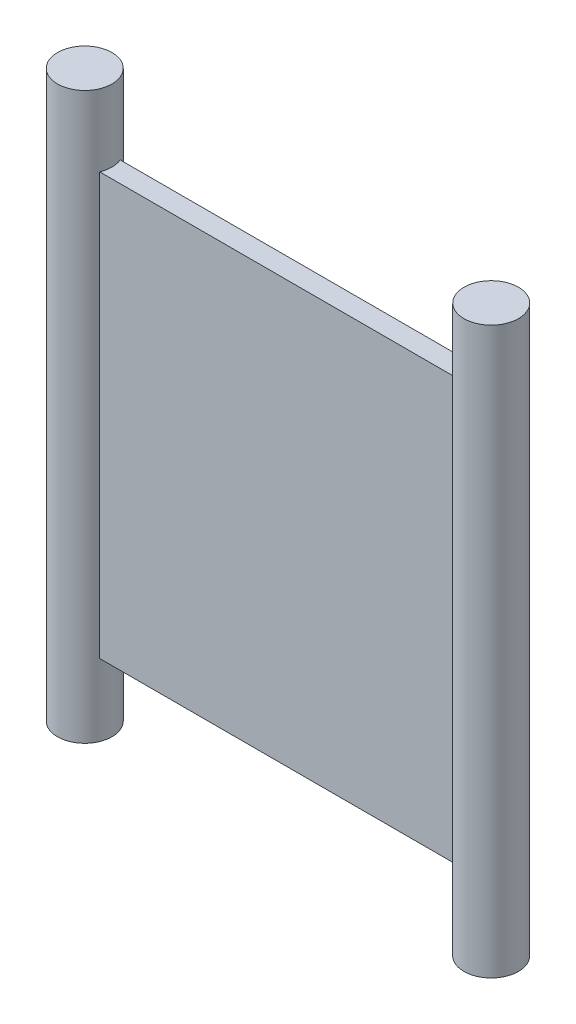
SolidWorks part; units mm, degrees
ref_plane "Front Plane" through (0, 0, 0) normal (0, 0, 1) x (1, 0, 0)
ref_plane "Top Plane" through (0, 0, 0) normal (0, 1, 0) x (1, 0, 0)
ref_plane "Right Plane" through (0, 0, 0) normal (1, 0, 0) x (0, 0, -1)
sketch "Sketch1" plane through (0, 0, 0) normal (0, 1, 0) x (1, 0, 0)
  line L1 (9.885, 0.5) -> (-9.885, 0.5)
  line L2 (9.885, 0.5) -> (9.885, -0.5)
  line L3 (9.885, -0.5) -> (-9.885, -0.5)
  line L4 (-9.885, 0.5) -> (-9.885, -0.5)
  line L5 (9.885, 0.5) -> (-9.885, -0.5) construction
  line L6 (9.885, -0.5) -> (-9.885, 0.5) construction
  point P0 (0, 0)
  dimension "D1" = 19.77
  dimension "D3" = 1
extrude "Boss-Extrude1" add sketch "Sketch1" along normal blind 20.5
ref_plane "Plane1" through (0, 10.25, 0) normal (0, 1, 0) x (1, 0, 0)
sketch "Sketch2" plane through (0, 10.25, 0) normal (0, 1, 0) x (1, 0, 0)
  line L0 (9.885, -0.5) -> (9.885, 0.5) construction
  line L1 (-9.885, 0.5) -> (-9.885, -0.5) construction
  line L2 (9.885, -0.5) -> (9.885, 0.5) construction
  line L3 (-9.885, 0.5) -> (-9.885, -0.5) construction
  circle A0 centre (-9.885, 0) radius 1.325
  circle A1 centre (9.885, 0) radius 1.325
  dimension "D1" = 2.65
extrude "Boss-Extrude2" add sketch "Sketch2" along normal mid plane 27.5
